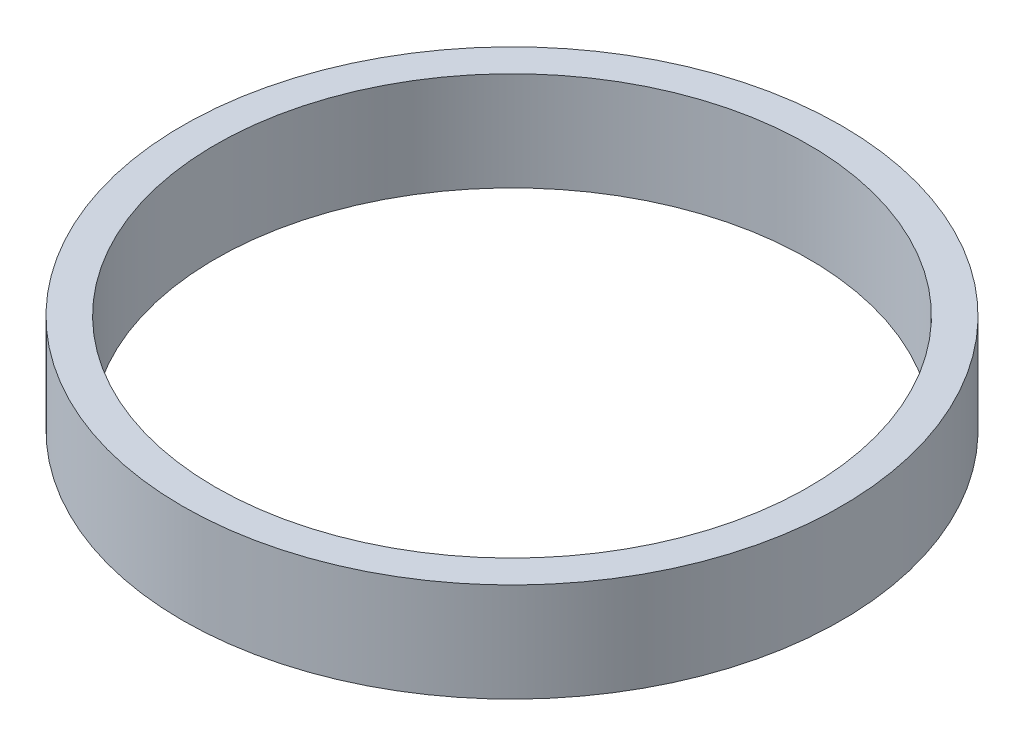
SolidWorks part; units mm, degrees
ref_plane "Front Plane" through (0, 0, 0) normal (0, 0, 1) x (1, 0, 0)
ref_plane "Top Plane" through (0, 0, 0) normal (0, 1, 0) x (1, 0, 0)
ref_plane "Right Plane" through (0, 0, 0) normal (1, 0, 0) x (0, 0, -1)
sketch "Sketch1" plane through (0, 0, 0) normal (0, 1, 0) x (1, 0, 0)
  circle A0 centre (0, 0) radius 10
extrude "Boss-Extrude1" add sketch "Sketch1" along normal blind 3
sketch "Sketch2" plane through (0, 3, 0) normal (0, 1, 0) x (1, 0, 0)
  circle A0 centre (0, 0) radius 9
extrude "Cut-Extrude1" cut sketch "Sketch2" against normal blind 3
